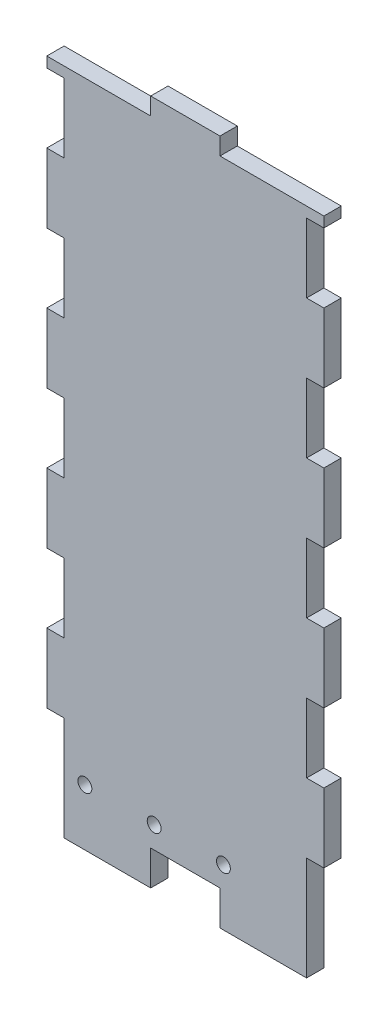
SolidWorks part; units mm, degrees
material "아크릴(내충격성)"
ref_plane "정면" through (0, 0, 0) normal (0, 0, 1) x (1, 0, 0)
ref_plane "윗면" through (0, 0, 0) normal (0, 1, 0) x (1, 0, 0)
ref_plane "우측면" through (0, 0, 0) normal (1, 0, 0) x (0, 0, -1)
sketch "스케치1" plane through (0, 0, 0) normal (0, 0, 1) x (1, 0, 0)
  line L1 (-40, 91.5) -> (40, 91.5)
  line L2 (-40, 91.5) -> (-40, -91.5)
  line L3 (-40, -91.5) -> (40, -91.5)
  line L4 (40, 91.5) -> (40, -91.5)
  line L5 (-40, 91.5) -> (40, -91.5) construction
  line L6 (-40, -91.5) -> (40, 91.5) construction
  point P0 (0, 0)
  dimension "D1" = 183
  dimension "D2" = 80
extrude "보스-돌출1" add sketch "스케치1" along normal blind 5
sketch "스케치2" plane through (0, 0, 5) normal (0, 0, 1) x (1, 0, 0)
  line L1 (-40, -91.5) -> (-35, -91.5)
  line L2 (-40, -91.5) -> (-40, -71.5)
  line L3 (-40, -71.5) -> (-35, -71.5)
  line L4 (-35, -91.5) -> (-35, -71.5)
  dimension "D1" = 5
  dimension "D2" = 20
extrude "컷-돌출1" cut sketch "스케치2" against normal up to next and the other way through all
pattern_linear "선형 패턴1" count 5 spacing 40 along (0, 1, 0) of "컷-돌출1"
sketch "스케치4" plane through (0, 0, 5) normal (0, 0, 1) x (1, 0, 0)
  line L1 (35, -91.5) -> (40, -91.5)
  line L2 (35, -91.5) -> (35, -71.5)
  line L3 (35, -71.5) -> (40, -71.5)
  line L4 (40, -91.5) -> (40, -71.5)
  dimension "D1" = 5
  dimension "D2" = 20
extrude "컷-돌출3" cut sketch "스케치4" against normal up to next
pattern_linear "선형 패턴4" count 5 spacing 40 along (0, 1, 0) of "컷-돌출3"
sketch "스케치5" plane through (0, 0, 5) normal (0, 0, 1) x (1, 0, 0)
  line L0 (40, 91.5) -> (-40, 91.5) construction
  line L1 (-10, 91.5) -> (10, 91.5)
  line L2 (-10, 91.5) -> (-10, 96.5)
  line L3 (-10, 96.5) -> (10, 96.5)
  line L4 (10, 91.5) -> (10, 96.5)
  line L5 (0, 159.4157) -> (0, 67.4362) construction
  point P10 (0, 113.4259)
  dimension "D1" = 5
  dimension "D2" = 20
extrude "보스-돌출2" add sketch "스케치5" against normal up to surface (5 mm away) up to face at (0, 7.65, 0)
sketch "스케치6" plane through (0, 0, 5) normal (0, 0, 1) x (1, 0, 0)
  line L0 (0, -80.4552) -> (0, -106.2956) construction
  line L1 (-35, -91.5) -> (35, -91.5) construction
  line L2 (-10, -101.5) -> (-35, -101.5)
  line L4 (10, -91.5) -> (10, -101.5)
  line L6 (-10, -91.5) -> (-10, -101.5)
  line L7 (-35, -101.5) -> (-35, -91.5)
  line L8 (-35, -91.5) -> (-10, -91.5)
  line L9 (10, -101.5) -> (35, -101.5)
  line L10 (35, -101.5) -> (35, -91.5)
  line L11 (35, -91.5) -> (10, -91.5)
  line L12 (-35, -71.5) -> (-35, -91.5) construction
  line L13 (35, -71.5) -> (35, -91.5) construction
  dimension "D1" = 20
  dimension "D2" = 10
extrude "보스-돌출3" add sketch "스케치6" against normal up to surface (5 mm away) up to face at (0, 15.5, 0)
sketch "스케치7" plane through (0, 0, 5) normal (0, 0, 1) x (1, 0, 0)
  line L0 (-35, -71.5) -> (-35, -101.5) construction
  line L1 (-10, -91.5) -> (10, -91.5) construction
  circle A0 centre (-29, -85.2) radius 2
  dimension "D3" = 4
  dimension "D1" = 6
  dimension "D2" = 6.3
extrude "컷-돌출4" cut sketch "스케치7" against normal up to next contours A0
pattern_linear "선형 패턴5" count 2 spacing 40 along (1, 0, 0) of "컷-돌출4"
pattern_linear "선형 패턴6" count 2 spacing 20 along (1, 0, 0) of "컷-돌출4"
